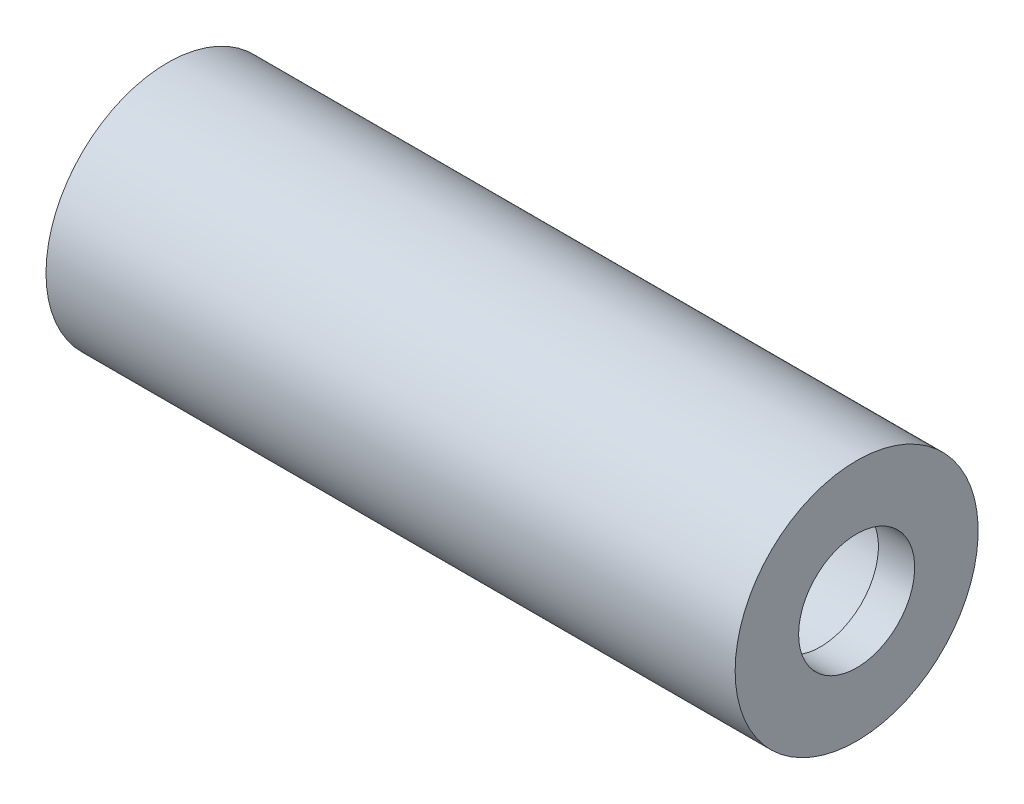
SolidWorks part; units mm, degrees
ref_plane "Front Plane" through (0, 0, 0) normal (0, 0, 1) x (1, 0, 0)
ref_plane "Top Plane" through (0, 0, 0) normal (0, 1, 0) x (1, 0, 0)
ref_plane "Right Plane" through (0, 0, 0) normal (1, 0, 0) x (0, 0, -1)
sketch "Sketch1" plane through (0, 0, 0) normal (0, 0, 1) x (1, 0, 0)
  line L0 (0, 0) -> (9326.5692, 0) construction
  line L1 (0, 3.35) -> (19, 3.35)
  line L2 (19, 3.35) -> (19, 1.6)
  line L3 (19, 1.6) -> (18, 1.6)
  line L4 (18, 1.6) -> (18, 2.35)
  line L5 (18, 2.35) -> (0, 2.35)
  line L6 (0, 2.35) -> (0, 3.35)
  point P5 (18.5, 1.6)
  dimension "D1" = 3.2
  dimension "D2" = 4.7
  dimension "D3" = 1
  dimension "D4" = 1
  dimension "D5" = 18
revolve "Revolve1" add sketch "Sketch1" angle 360 about L0
